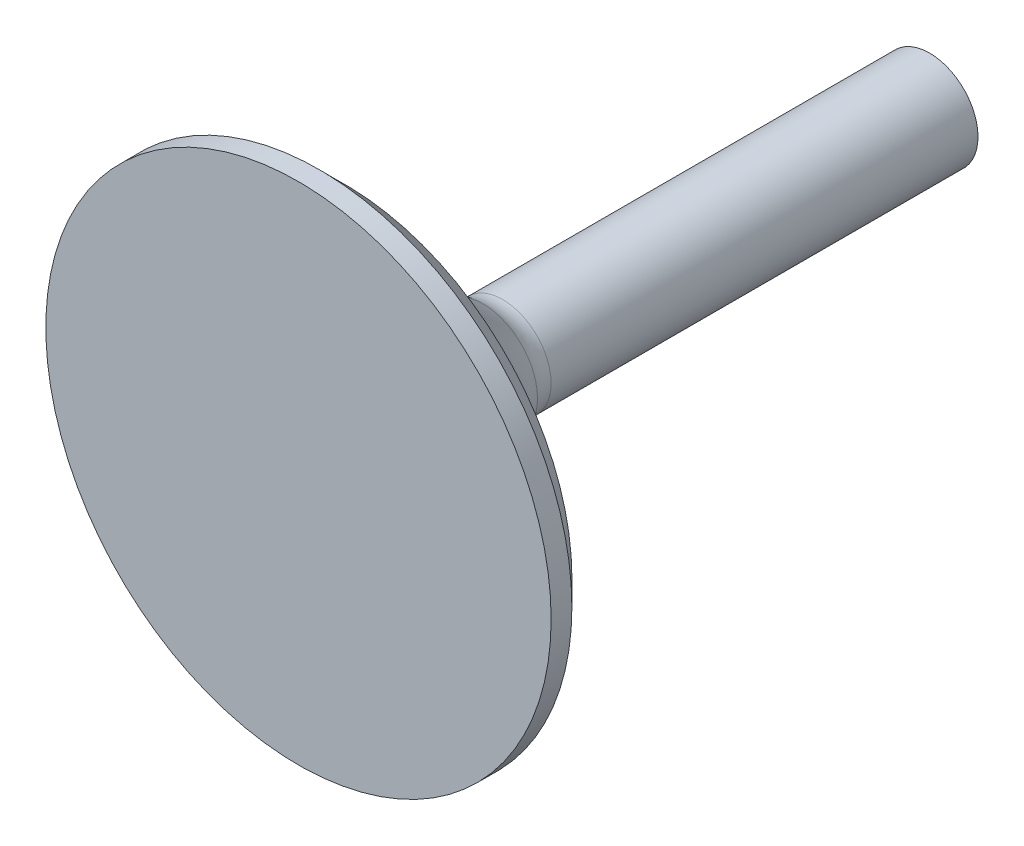
SolidWorks part; units mm, degrees
ref_plane "Front Plane" through (0, 0, 0) normal (0, 0, 1) x (1, 0, 0)
ref_plane "Top Plane" through (0, 0, 0) normal (0, 1, 0) x (1, 0, 0)
ref_plane "Right Plane" through (0, 0, 0) normal (1, 0, 0) x (0, 0, -1)
sketch "Sketch1" plane through (0, 0, 0) normal (0, 1, 0) x (1, 0, 0)
  line L0 (0, 17.0482) -> (0, -25.5721) construction
  line L1 (0, -25.5721) -> (18.5738, -25.5721)
  line L2 (18.5738, -25.5721) -> (18.5738, -24.0466)
  line L3 (18.5738, -24.0466) -> (16.6846, -22.1575)
  line L4 (3.556, -10.558) -> (3.556, 20.8232)
  line L5 (0, -25.5721) -> (0, 20.8232)
  line L6 (0, 20.8232) -> (3.556, 20.8232)
  arc A0 (3.556, -10.558) -> (4.0207, -12.0224) centre (6.096, -10.558) ccw
  spline S0 degree 3 poles (16.6846, -22.1575) (11.4681, -19.9625) (7.226, -16.5649) (4.0207, -12.0224) knots 0 0 0 0 0.953212 0.953212 0.953212 0.953212
  dimension "D5" = 2.54
  dimension "D1" = 18.5738
  dimension "D2" = 16.6846
  dimension "D3" = 45
  dimension "D4" = 7.112
revolve "Revolve1" add sketch "Sketch1" angle 360 about L5
